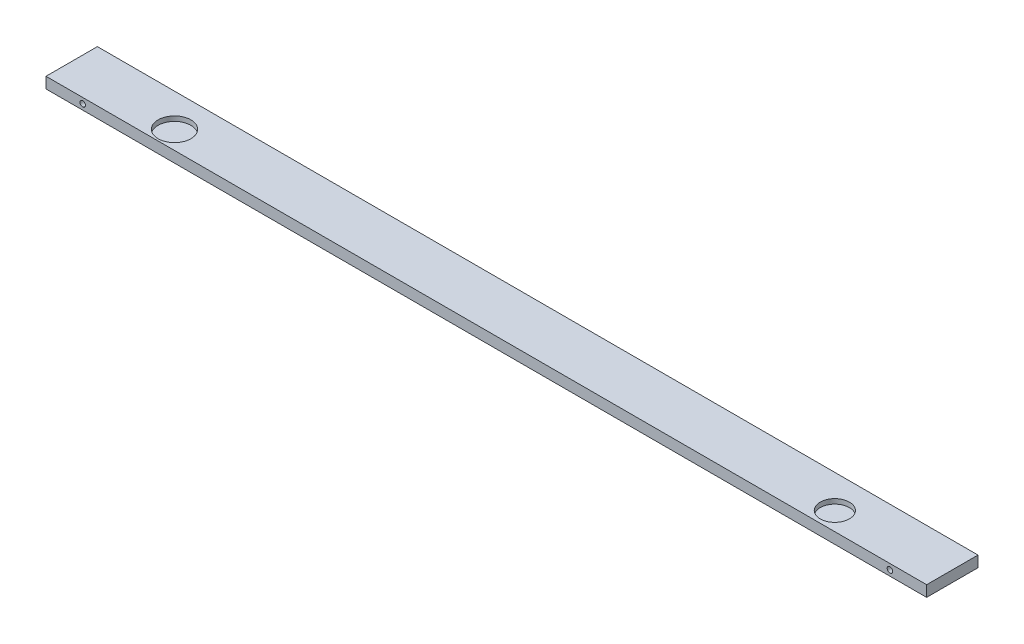
SolidWorks part; units mm, degrees
ref_plane "Alzado" through (0, 0, 0) normal (0, 0, 1) x (1, 0, 0)
ref_plane "Planta" through (0, 0, 0) normal (0, 1, 0) x (1, 0, 0)
ref_plane "Vista lateral" through (0, 0, 0) normal (1, 0, 0) x (0, 0, -1)
sketch "Croquis1" plane through (0, 0, 0) normal (0, 1, 0) x (1, 0, 0)
  line L1 (120, -7) -> (-120, -7)
  line L2 (120, -7) -> (120, 7)
  line L3 (120, 7) -> (-120, 7)
  line L4 (-120, -7) -> (-120, 7)
  line L5 (120, -7) -> (-120, 7) construction
  line L6 (120, 7) -> (-120, -7) construction
  point P0 (0, 0)
  dimension "D1" = 240
  dimension "D2" = 14
extrude "Saliente-Extruir2" add sketch "Croquis1" along normal blind 3 contours L2 L1 L4 L3
sketch "Croquis3" plane through (0, 3, 0) normal (0, 1, 0) x (1, 0, 0)
  line L0 (120, -7) -> (-120, -7) construction
  circle A0 centre (-89.9778, -2) radius 4.4663
  circle A1 centre (89.9778, -2) radius 3.9701
  point P7 (-3.4738, 4.2274)
  dimension "D3" = 5
  dimension "D1" = 90
  dimension "D2" = 90
  dimension "D4" = 5
extrude "Cortar-Extruir1" cut sketch "Croquis3" against normal blind 1.3
sketch "Croquis4" plane through (0, 0, -7) normal (0, 0, -1) x (-1, 0, 0)
  line L0 (-120, 1.5) -> (120, 1.5) construction
  line L1 (-120, 3) -> (-120, 0) construction
  line L2 (120, 3) -> (120, 0) construction
  line L3 (0, 1.65) -> (0, -1.65) construction
  circle A0 centre (-110, 1.5) radius 0.75
  circle A1 centre (110, 1.5) radius 0.75
  dimension "D1" = 1.5
  dimension "D2" = 10
extrude "Cortar-Extruir2" cut sketch "Croquis4" against normal through all
